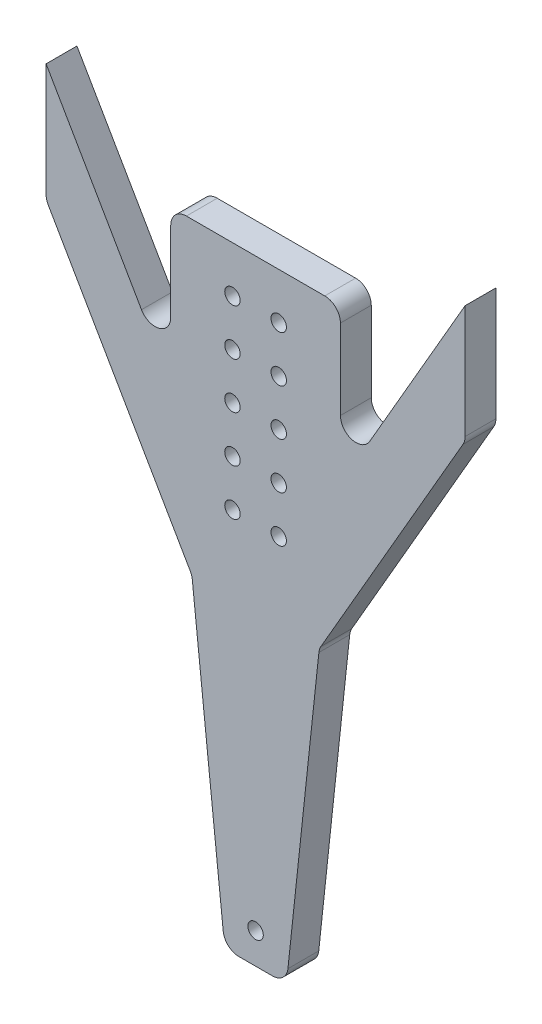
SolidWorks part; units mm, degrees
ref_plane "Plan de face" through (0, 0, 0) normal (0, 0, 1) x (1, 0, 0)
ref_plane "Plan de dessus" through (0, 0, 0) normal (0, 1, 0) x (1, 0, 0)
ref_plane "Plan de droite" through (0, 0, 0) normal (1, 0, 0) x (0, 0, -1)
sketch "Sketch1" plane through (0, 0, 0) normal (0, 0, 1) x (1, 0, 0)
  line L19 (27.5105, 50) -> (67.925, 120)
  line L21 (67.925, 81.9) -> (20.64, 0)
  line L23 (20.64, 0) -> (10, -99.4323)
  line L24 (10, -99.4323) -> (-10, -99.4323)
  line L25 (-10, -99.4323) -> (-20.64, 0)
  line L26 (-20.64, 0) -> (-67.925, 81.9)
  line L28 (-67.925, 120) -> (-27.5105, 50)
  line L29 (-20.64, 0) -> (20.64, 0) construction
  line L30 (-67.925, 120) -> (-67.925, 81.9)
  line L31 (67.925, 120) -> (67.925, 81.9)
  line L32 (-27.5105, 50) -> (-27.5105, 100)
  line L33 (-27.5105, 100) -> (27.5105, 100)
  line L34 (27.5105, 100) -> (27.5105, 50)
  point P18 (0, -99.4323)
  dimension "D1" = 41.28
  dimension "D2" = 19.05
  dimension "D3" = 60
  dimension "D4" = 120
  dimension "D5" = 100
  dimension "D7" = 20
  dimension "D8" = 19.05
  dimension "D9" = 67.925
  dimension "D10" = 50
extrude "Boss-Extrude1" add sketch "Sketch1" along normal blind 10
fillet "Fillet1" radius 5.08 10 edges at (-10, -99.4323, 5) (10, -99.4323, 5) (20.64, 0, 5) (-20.64, 0, 5) (67.925, 81.9, 5) (-67.925, 81.9, 5) (27.5105, 50, 5) (-27.5105, 50, 5) (27.5105, 100, 5) (-27.5105, 100, 5)
hole_wizard "Ø5.0mm Dowel Hole1" positions "Sketch12" profile "Sketch13" hole size "Ø5.0" standard "ANSI Metric" end condition through all
sketch "Sketch12" plane through (0, 0, 0) normal (0, 0, -1) x (-1, 0, 0)
  line L14 (-7.5, 25) -> (7.5, 25) construction
  point P83 (7.5, 25)
  point P89 (-7.5, 25)
  point P116 (0, 25)
  dimension "D1" = 15
  dimension "D2" = 25
sketch "Sketch13" plane through (-7.5, 25, 0) normal (1, 0, 0) x (0, 1, 0)
  line L0 (0, 0) -> (0, 10)
  line L1 (0, 10) -> (2.5, 10)
  line L2 (2.5, 10) -> (2.5, 0)
  line L5 (2.5, 0) -> (0, 0)
  line L11 (0, -6.35) -> (0, 107.95) construction
  dimension "Thru Hole Dia." = 5
  dimension "Thru Hole Depth" = 10
sketch "Sketch14" plane through (0, 0, 10) normal (0, 0, 1) x (1, 0, 0)
  line L0 (-5.4346, -99.4323) -> (5.4346, -99.4323) construction
  circle A0 centre (0, -89.4323) radius 2.5
  dimension "D1" = 5
  dimension "D2" = 10
extrude "Cut-Extrude1" cut sketch "Sketch14" against normal through all
pattern_linear "LPattern1" count 5 spacing 15 along (0, 1, 0) of "Ø5.0mm Dowel Hole1"
